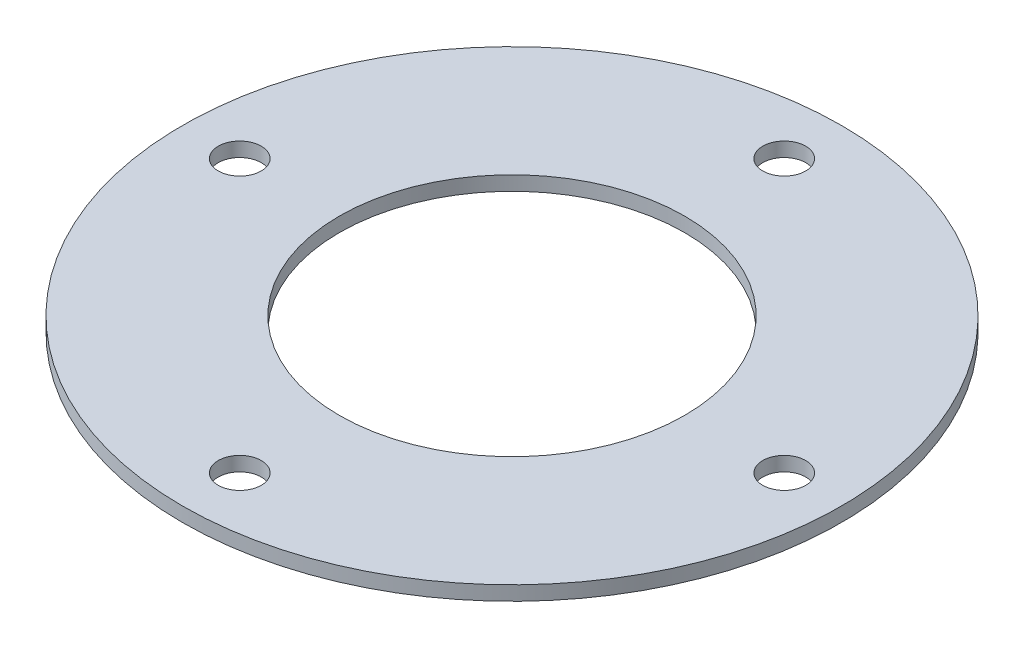
SolidWorks part; units mm, degrees
material "1023 Carbon Steel Sheet (SS)"
ref_plane "Front Plane" through (0, 0, 0) normal (0, 0, 1) x (1, 0, 0)
ref_plane "Top Plane" through (0, 0, 0) normal (0, 1, 0) x (1, 0, 0)
ref_plane "Right Plane" through (0, 0, 0) normal (1, 0, 0) x (0, 0, -1)
sketch "Sketch1" plane through (0, 0, 0) normal (0, 1, 0) x (1, 0, 0)
  circle A0 centre (0, 0) radius 12.05
  circle A2 centre (0, 19) radius 1.5
  circle A3 centre (19, 0) radius 1.5
  circle A4 centre (0, -19) radius 1.5
  circle A5 centre (-19, 0) radius 1.5
  circle A7 centre (0, 0) radius 23
  point P16 (0, 0)
  point P17 (0, 0)
  point P18 (0, 0)
  dimension "D1" = 24.1
  dimension "D3" = 3
  dimension "D4" = 4
  dimension "D6" = 46
extrude "Boss-Extrude1" add sketch "Sketch1" along normal blind 1
